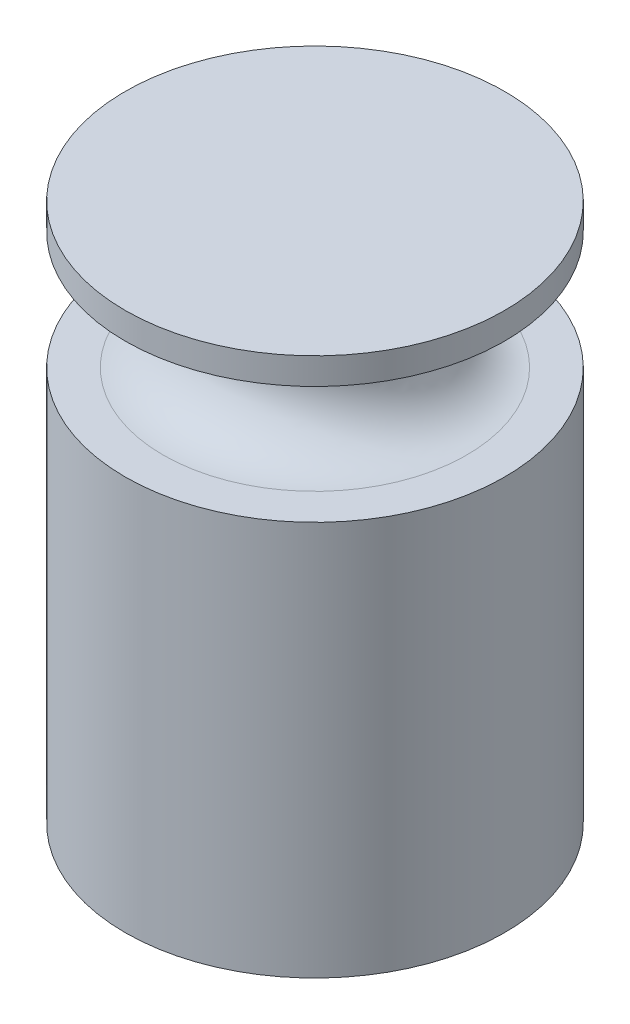
SolidWorks part; units mm, degrees
material "Plain Carbon Steel"
ref_plane "Front Plane" through (0, 0, 0) normal (0, 0, 1) x (1, 0, 0)
ref_plane "Top Plane" through (0, 0, 0) normal (0, 1, 0) x (1, 0, 0)
ref_plane "Right Plane" through (0, 0, 0) normal (1, 0, 0) x (0, 0, -1)
sketch "Sketch1" plane through (0, 0, 0) normal (0, 0, 1) x (1, 0, 0)
  line L0 (0, 0) -> (25, 0)
  line L1 (55, 0) -> (-55, 0) construction
  line L2 (25, 0) -> (25, 52)
  line L3 (20, 67.5) -> (25, 67.5)
  line L4 (25, 52) -> (20, 52)
  line L6 (25, 67.5) -> (25, 71)
  line L7 (25, 71) -> (0, 71)
  line L8 (0, -55) -> (0, 55) construction
  line L9 (0, 71) -> (0, 0)
  line L10 (0, 52.6038) -> (0, -11.8802) construction
  arc A0 (20, 67.5) -> (20, 52) centre (20, 59.75) ccw
  dimension "D6" = 15.5
  dimension "D1" = 71
  dimension "D2" = 25
  dimension "D3" = 3.5
  dimension "D4" = 15.5
  dimension "D5" = 7.75
  dimension "D7" = 5
revolve "Revolve1" add sketch "Sketch1" angle 360 about L10
